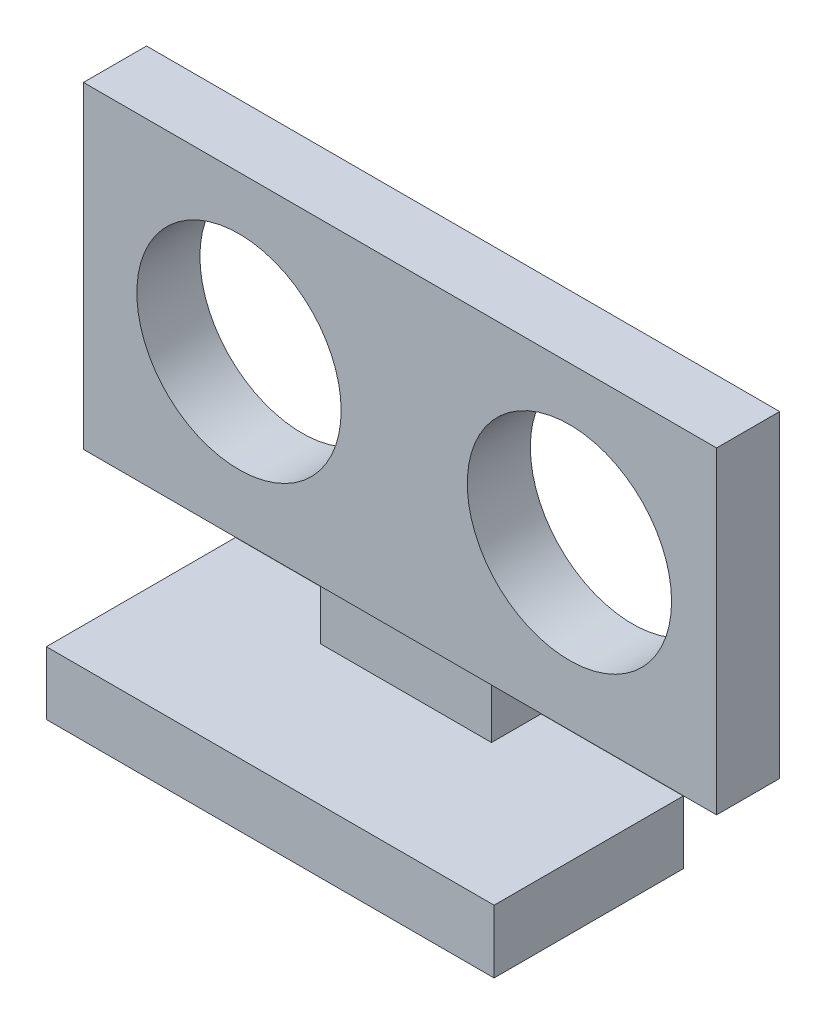
SolidWorks part; units mm, degrees
ref_plane "Front Plane" through (0, 0, 0) normal (0, 0, 1) x (1, 0, 0)
ref_plane "Top Plane" through (0, 0, 0) normal (0, 1, 0) x (1, 0, 0)
ref_plane "Right Plane" through (0, 0, 0) normal (1, 0, 0) x (0, 0, -1)
sketch "Sketch1" plane through (0, 0, 0) normal (0, 1, 0) x (1, 0, 0)
  line L0 (14.5041, 9.9599) -> (50.0041, 9.9599)
  line L5 (14.5041, 21.2754) -> (50.0041, 21.2754)
  line L10 (14.5041, 21.2754) -> (14.5041, 6.2754)
  line L11 (14.5041, 6.2754) -> (50.0041, 6.2754)
  line L12 (50.0041, 21.2754) -> (50.0041, 6.2754)
  line L13 (14.5041, 14.0701) -> (50.0041, 14.1179)
  dimension "D1" = 35.5
  dimension "D2" = 15
extrude "Boss-Extrude7" add sketch "Sketch1" along normal blind 5
sketch "Sketch5" plane through (0, 5, 0) normal (0, 1, 0) x (1, 0, 0)
  line L0 (14.5041, 21.2754) -> (50.0041, 21.2754) construction
  line L1 (25.1665, 21.2754) -> (38.7336, 21.2754)
  line L2 (25.1665, 21.2754) -> (25.1665, 17.3426)
  line L3 (25.1665, 17.3426) -> (38.7336, 17.3426)
  line L4 (38.7336, 21.2754) -> (38.7336, 17.3426)
extrude "Boss-Extrude8" add sketch "Sketch5" along normal blind 5
sketch "Sketch6" plane through (1.1246, 10, 0) normal (0, 1, 0) x (1, 0, 0)
  line L2 (6.3022, 21.2948) -> (56.5022, 21.2948)
  line L3 (6.3022, 21.2948) -> (6.3022, 16.2948)
  line L4 (6.3022, 16.2948) -> (56.5022, 16.2948)
  line L5 (56.5022, 21.2948) -> (56.5022, 16.2948)
  dimension "D1" = 50.2
  dimension "D2" = 5
extrude "Boss-Extrude9" add sketch "Sketch6" along normal blind 25.2 contours L3 L2 L5 L4
sketch "Sketch7" plane through (0, 0, -16.2948) normal (0, 0, 1) x (1, 0, 0)
  line L0 (19.7589, 22.8759) -> (45.9589, 22.8759)
  circle A0 centre (19.7589, 22.8759) radius 8.1
  circle A1 centre (45.9589, 22.8759) radius 8.1
  dimension "D1" = 16.2
  dimension "D2" = 26.2
extrude "Cut-Extrude1" cut sketch "Sketch7" against normal blind 10
